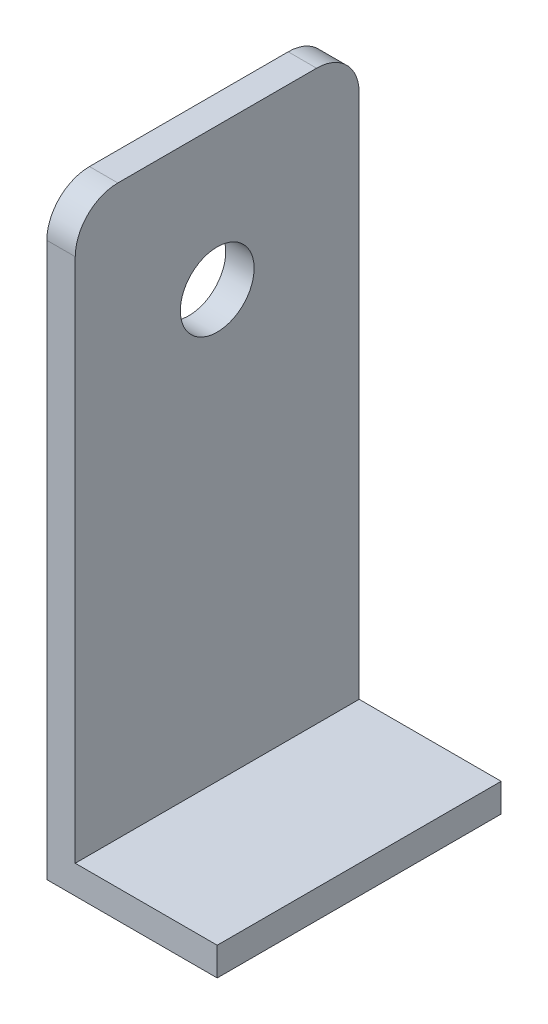
SolidWorks part; units mm, degrees
ref_plane "前视基准面" through (0, 0, 0) normal (0, 0, 1) x (1, 0, 0)
ref_plane "上视基准面" through (0, 0, 0) normal (0, 1, 0) x (1, 0, 0)
ref_plane "右视基准面" through (0, 0, 0) normal (1, 0, 0) x (0, 0, -1)
sketch "草图1" plane through (0, 0, 0) normal (0, 0, 1) x (1, 0, 0)
  line L0 (0, 40) -> (0, 0)
  line L1 (0, 0) -> (10, 0)
  dimension "D1" = 40
  dimension "D2" = 10
extrude "拉伸-薄壁1" add sketch "草图1" along normal blind 20 thin
sketch "草图2" plane through (0, 0, 0) normal (1, 0, 0) x (0, 0, -1)
  line L0 (-10, 40) -> (-10, -3.0107) construction
  line L1 (-20, 40) -> (0, 40) construction
  circle A0 centre (-10, 30) radius 2.6
  dimension "D1" = 5.2
  dimension "D2" = 10
extrude "切除-拉伸1" cut sketch "草图2" against normal blind 10
fillet "圆角1" radius 3 2 edges at (-1, 40, 20) (-1, 40, 0)
